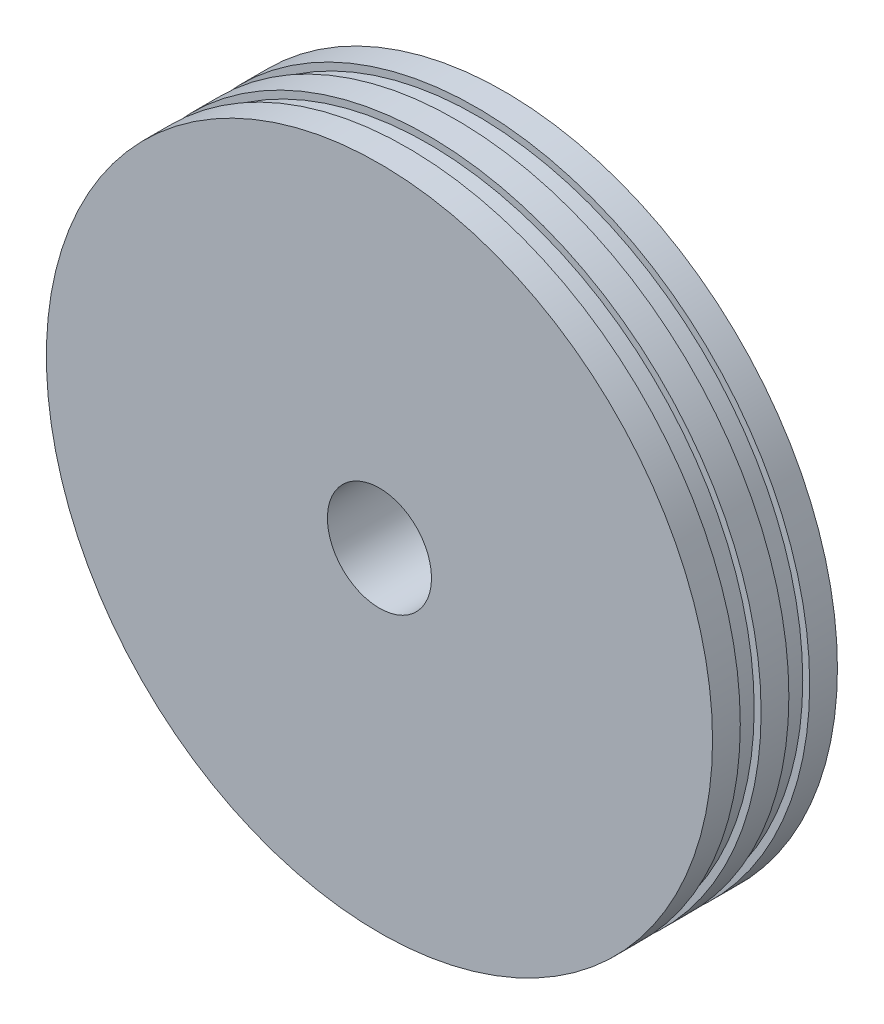
SolidWorks part; units mm, degrees
material "AISI 316 Stainless Steel Sheet (SS)"
ref_plane "Front Plane" through (0, 0, 0) normal (0, 0, 1) x (1, 0, 0)
ref_plane "Top Plane" through (0, 0, 0) normal (0, 1, 0) x (1, 0, 0)
ref_plane "Right Plane" through (0, 0, 0) normal (1, 0, 0) x (0, 0, -1)
sketch "Sketch1" plane through (0, 0, 0) normal (0, 0, 1) x (1, 0, 0)
  circle A0 centre (0, 0) radius 120
  dimension "D1" = 240
extrude "Boss-Extrude2" add sketch "Sketch1" along normal blind 10
sketch "Sketch2" plane through (0, 0, 10) normal (0, 0, 1) x (1, 0, 0)
  circle A0 centre (0, 0) radius 117.5
  dimension "D1" = 235
extrude "Boss-Extrude3" add sketch "Sketch2" along normal blind 7.5
sketch "Sketch3" plane through (0, 0, 17.5) normal (0, 0, 1) x (1, 0, 0)
  circle A0 centre (0, 0) radius 120
extrude "Boss-Extrude4" add sketch "Sketch3" along normal blind 10
sketch "Sketch4" plane through (0, 0, 27.5) normal (0, 0, 1) x (1, 0, 0)
  circle A0 centre (0, 0) radius 117.5
  dimension "D1" = 235
extrude "Boss-Extrude5" add sketch "Sketch4" along normal blind 7.5 contours A0
sketch "Sketch5" plane through (0, 0, 35) normal (0, 0, 1) x (1, 0, 0)
  circle A0 centre (0, 0) radius 120
extrude "Boss-Extrude6" add sketch "Sketch5" along normal blind 10
sketch "Sketch6" plane through (0, 0, 45) normal (0, 0, 1) x (1, 0, 0)
  circle A0 centre (0, 0) radius 18.75
  dimension "D1" = 37.5
extrude "Cut-Extrude1" cut sketch "Sketch6" against normal blind 50
